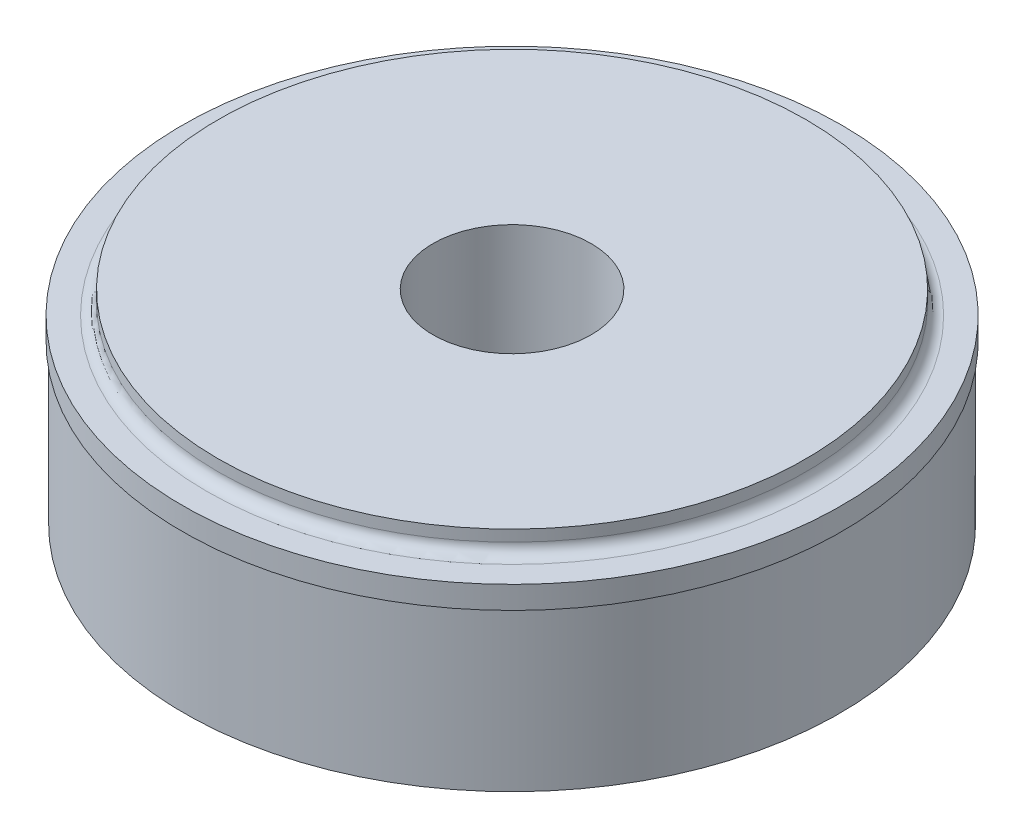
SolidWorks part; units mm, degrees
material "延性铁"
ref_plane "前视基准面" through (0, 0, 0) normal (0, 0, 1) x (1, 0, 0)
ref_plane "上视基准面" through (0, 0, 0) normal (0, 1, 0) x (1, 0, 0)
ref_plane "右视基准面" through (0, 0, 0) normal (1, 0, 0) x (0, 0, -1)
sketch "草图1" plane through (0, 0, 0) normal (1, 0, 0) x (0, 0, -1)
  line L0 (0, 0) -> (0, 38.8583) construction
  line L1 (-17.5, 45) -> (-17.5, 0)
  line L2 (-17.5, 0) -> (-72.5, 0)
  line L3 (-72.5, 0) -> (-72.5, 35)
  line L4 (-72.5, 35) -> (-72.9, 35)
  line L5 (-72.9, 35) -> (-72.9, 40)
  line L6 (-72.9, 40) -> (-67.5, 40)
  line L7 (-65, 42.5) -> (-65, 45)
  line L8 (-65, 45) -> (-17.5, 45)
  arc A0 (-67.5, 40) -> (-65, 42.5) centre (-67.5, 42.5) ccw
  point P13 (-65, 40)
  dimension "D8" = 2.5
  dimension "D1" = 35
  dimension "D2" = 145.8
  dimension "D3" = 145
  dimension "D4" = 130
  dimension "D5" = 5
  dimension "D6" = 5
  dimension "D7" = 45
revolve "旋转1" add sketch "草图1" angle 360 about L0
